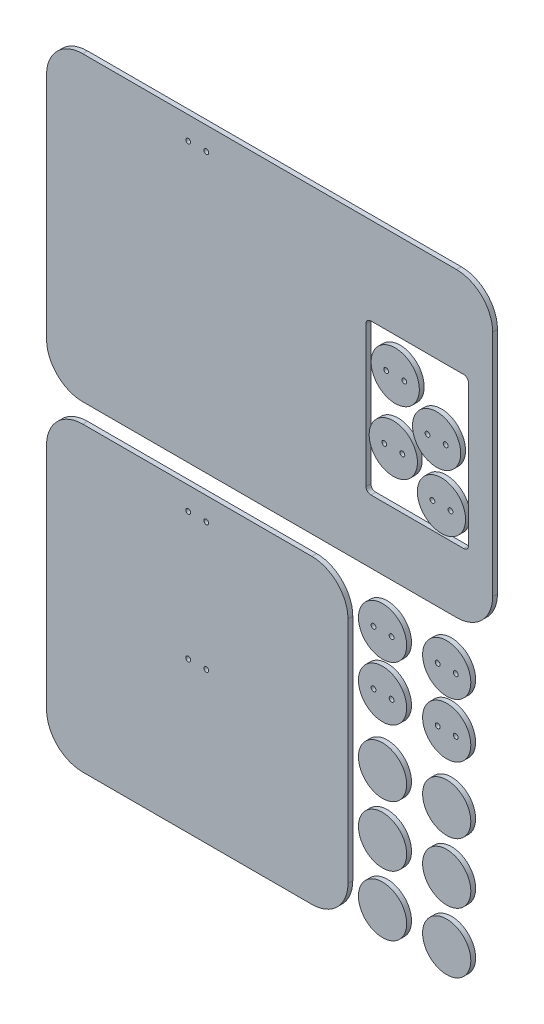
SolidWorks part; units mm, degrees
ref_plane "Front Plane" through (0, 0, 0) normal (0, 0, 1) x (1, 0, 0)
ref_plane "Top Plane" through (0, 0, 0) normal (0, 1, 0) x (1, 0, 0)
ref_plane "Right Plane" through (0, 0, 0) normal (1, 0, 0) x (0, 0, -1)
sketch "Sketch1" plane through (0, 0, 0) normal (0, 0, 1) x (1, 0, 0)
  line L0 (-176.2722, -263.1741) -> (73.7278, -263.1741) construction
  line L1 (163.7278, 127.8615) -> (-146.2722, 127.8615)
  line L2 (193.7278, 97.8615) -> (193.7278, -92.1385)
  line L3 (163.7278, -122.1385) -> (-146.2722, -122.1385)
  line L4 (-176.2722, 97.8615) -> (-176.2722, -92.1385)
  line L5 (43.7278, -138.1741) -> (-146.2722, -138.1741)
  line L6 (73.7278, -168.1741) -> (73.7278, -358.1741)
  line L7 (43.7278, -388.1741) -> (-146.2722, -388.1741)
  line L8 (-176.2722, -168.1741) -> (-176.2722, -358.1741)
  line L9 (169.7278, 55.4306) -> (92.7278, 55.4306)
  line L10 (173.7278, 51.4306) -> (173.7278, -65.5694)
  line L11 (169.7278, -69.5694) -> (92.7278, -69.5694)
  line L12 (88.7278, 51.4306) -> (88.7278, -65.5694)
  line L13 (-58.7722, -157.1741) -> (-43.7722, -157.1741) construction
  line L14 (-58.7722, -157.1741) -> (-58.7722, -263.1741) construction
  line L15 (-58.7722, -263.1741) -> (-43.7722, -263.1741) construction
  line L16 (-43.7722, -157.1741) -> (-43.7722, -263.1741) construction
  line L17 (94.924, -162.7624) -> (109.924, -162.7624) construction
  line L18 (148.1295, -162.7624) -> (163.1295, -162.7624) construction
  line L19 (94.924, -207.7624) -> (109.924, -207.7624) construction
  line L20 (148.1295, -207.7624) -> (163.1295, -207.7624) construction
  line L21 (105.4397, 26.1629) -> (120.4397, 26.1629) construction
  line L22 (139.7501, -2.4956) -> (154.7501, -2.4956) construction
  line L23 (103.8448, -26.9781) -> (118.8448, -26.9781) construction
  line L24 (143.7868, -47.9646) -> (158.7868, -47.9646) construction
  line L25 (-176.2722, 2.8615) -> (193.7278, 2.8615) construction
  line L27 (-58.7722, 2.8615) -> (-43.7722, 2.8615) construction
  line L28 (-58.7722, 2.8615) -> (-58.7722, 108.8615) construction
  line L29 (-58.7722, 108.8615) -> (-43.7722, 108.8615) construction
  line L30 (-43.7722, 2.8615) -> (-43.7722, 108.8615) construction
  circle A0 centre (102.424, -162.7624) radius 20
  circle A2 centre (155.6295, -162.7624) radius 20
  arc A6 (193.7278, -92.1385) -> (163.7278, -122.1385) centre (163.7278, -92.1385) cw
  arc A7 (163.7278, 127.8615) -> (193.7278, 97.8615) centre (163.7278, 97.8615) cw
  arc A8 (-146.2722, 127.8615) -> (-176.2722, 97.8615) centre (-146.2722, 97.8615) ccw
  arc A9 (-146.2722, -122.1385) -> (-176.2722, -92.1385) centre (-146.2722, -92.1385) cw
  arc A10 (-146.2722, -388.1741) -> (-176.2722, -358.1741) centre (-146.2722, -358.1741) cw
  arc A11 (73.7278, -358.1741) -> (43.7278, -388.1741) centre (43.7278, -358.1741) cw
  arc A12 (43.7278, -138.1741) -> (73.7278, -168.1741) centre (43.7278, -168.1741) cw
  arc A13 (-146.2722, -138.1741) -> (-176.2722, -168.1741) centre (-146.2722, -168.1741) ccw
  arc A14 (92.7278, -69.5694) -> (88.7278, -65.5694) centre (92.7278, -65.5694) cw
  arc A15 (173.7278, -65.5694) -> (169.7278, -69.5694) centre (169.7278, -65.5694) cw
  arc A16 (169.7278, 55.4306) -> (173.7278, 51.4306) centre (169.7278, 51.4306) cw
  arc A17 (92.7278, 55.4306) -> (88.7278, 51.4306) centre (92.7278, 51.4306) ccw
  circle A22 centre (102.424, -262.7624) radius 20
  circle A23 centre (155.6295, -262.7624) radius 20
  circle A24 centre (102.424, -312.7624) radius 20
  circle A25 centre (155.6295, -312.7624) radius 20
  circle A26 centre (102.424, -362.7624) radius 20
  circle A27 centre (155.6295, -362.7624) radius 20
  circle A28 centre (-58.7722, -157.1741) radius 2
  circle A29 centre (-43.7722, -157.1741) radius 2
  circle A30 centre (-43.7722, -263.1741) radius 2
  circle A31 centre (-58.7722, -263.1741) radius 2
  circle A32 centre (94.924, -162.7624) radius 2
  circle A33 centre (109.924, -162.7624) radius 2
  circle A34 centre (148.1295, -162.7624) radius 2
  circle A35 centre (163.1295, -162.7624) radius 2
  circle A36 centre (155.6295, -212.7624) radius 20 [skipped]
  circle A37 centre (102.424, -212.7624) radius 20 [skipped]
  circle A38 centre (102.424, -207.7624) radius 20
  circle A39 centre (155.6295, -207.7624) radius 20
  circle A40 centre (94.924, -207.7624) radius 2
  circle A41 centre (109.924, -207.7624) radius 2
  circle A42 centre (148.1295, -207.7624) radius 2
  circle A43 centre (163.1295, -207.7624) radius 2
  circle A44 centre (112.9397, 26.1629) radius 20
  circle A45 centre (147.2501, -2.4956) radius 20
  circle A46 centre (105.4397, 26.1629) radius 2
  circle A47 centre (120.4397, 26.1629) radius 2
  circle A48 centre (139.7501, -2.4956) radius 2
  circle A49 centre (154.7501, -2.4956) radius 2
  circle A50 centre (111.3448, -26.9781) radius 20
  circle A51 centre (151.2868, -47.9646) radius 20
  circle A56 centre (-58.7722, 108.8615) radius 2
  circle A57 centre (-43.7722, 108.8615) radius 2
  circle A58 centre (118.8448, -26.9781) radius 2
  circle A59 centre (103.8448, -26.9781) radius 2
  circle A60 centre (143.7868, -47.9646) radius 2
  circle A61 centre (158.7868, -47.9646) radius 2
  point P27 (193.7278, -122.1385)
  point P30 (193.7278, 127.8615)
  point P35 (-176.2722, -122.1385)
  point P38 (-176.2722, -388.1741)
  point P41 (73.7278, -388.1741)
  point P46 (-176.2722, -138.1741)
  point P49 (88.7278, -69.5694)
  point P52 (173.7278, -69.5694)
  point P57 (88.7278, 55.4306)
  point P75 (-51.2722, -263.1741)
  point P76 (-51.2722, -263.1741)
  point P79 (102.424, -162.7624)
  point P82 (155.6295, -162.7624)
  point P94 (102.424, -207.7624)
  point P97 (155.6295, -207.7624)
  point P112 (112.9397, 26.1629)
  point P115 (147.2501, -2.4956)
  point P123 (111.3448, -26.9781)
  point P124 (111.3448, -26.9781)
  point P126 (151.2868, -47.9646)
  point P128 (151.2868, -47.9646)
  point P139 (151.2868, -47.9646)
  point P140 (111.3448, -26.9781)
  point P141 (112.9397, 26.1629)
  dimension "D9" = 30
  dimension "D10" = 30
  dimension "D11" = 4
  dimension "D15" = 4
  dimension "D18" = 4
  dimension "D22" = 4
  dimension "D25" = 4
  dimension "D26" = 4
  dimension "D2" = 250
  dimension "D3" = 370
  dimension "D4" = 85
  dimension "D5" = 125
  dimension "D6" = 250
  dimension "D7" = 250
  dimension "D8" = 20
  dimension "D13" = 15
  dimension "D14" = 106
  dimension "D16" = 15
  dimension "D17" = 15
  dimension "D20" = 15
  dimension "D21" = 15
  dimension "D23" = 15
  dimension "D24" = 106
  dimension "D27" = 15
  dimension "D28" = 15
  dimension "D29" = 117.5
  dimension "D12" = 5
  dimension "D19" = 2
extrude "Boss-Extrude1" add sketch "Sketch1" along normal blind 4 contours A9 L3 A6 L2 A7 L1 A8 L4 A57 A56 A17 L9 A16 L10 A15 L11 A14 L12 | A50 A59 A58 | A45 A49 A48 | A44 A47 A46 | A51 A61 A60 | L5 A13 L8 A10 L7 A11 L6 A12 A31 A30 A29 A28 | A0 A33 A32 | A2 A35 A34 | A38 A41 A40 | A39 A43 A42 | A22 | A23 | A24 | A25 | A26 | A27
